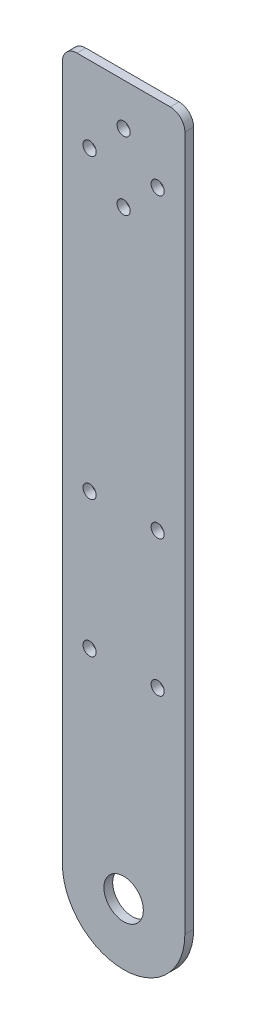
SolidWorks part; units mm, degrees
ref_plane "Plano frontal" through (0, 0, 0) normal (0, 0, 1) x (1, 0, 0)
ref_plane "Plano superior" through (0, 0, 0) normal (0, 1, 0) x (1, 0, 0)
ref_plane "Plano direito" through (0, 0, 0) normal (1, 0, 0) x (0, 0, -1)
sketch "Esboço1" plane through (0, 0, 0) normal (0, 0, 1) x (1, 0, 0)
  line L0 (-12.5962, 0) -> (-12.5962, 145.8324)
  line L1 (-12.5962, 145.8324) -> (12.5962, 145.8324)
  line L2 (12.5962, 145.8324) -> (12.5962, 0)
  line L3 (0, 145.8324) -> (0, -20.2118) construction
  line L4 (12.5962, 130.1858) -> (-12.5962, 130.1858) construction
  arc A0 (-12.5962, 0) -> (12.5962, 0) centre (0, 0) ccw
  circle A1 centre (7, 41.09) radius 1.35
  circle A2 centre (7, 69.09) radius 1.35
  circle A3 centre (-7, 41.09) radius 1.35
  circle A4 centre (-7, 69.09) radius 1.35
  circle A5 centre (7, 130.1858) radius 1.35
  circle A6 centre (0, 137.1858) radius 1.35
  circle A7 centre (-7, 130.1858) radius 1.35
  circle A8 centre (0, 123.1858) radius 1.35
  circle A9 centre (0, 0) radius 4.05
  dimension "D1" = 7
  dimension "D2" = 7
  dimension "D3" = 2.7
  dimension "D4" = 2.7
  dimension "D5" = 2.7
  dimension "D6" = 2.7
  dimension "D7" = 28
extrude "Ressalto-extrusão1" add sketch "Esboço1" along normal blind 1.8
fillet "Filete1" radius 3 1 edges at (12.5962, 145.8324, 0.9)
fillet "Filete3" radius 3 1 edges at (-12.5962, 145.8324, 0.9)
